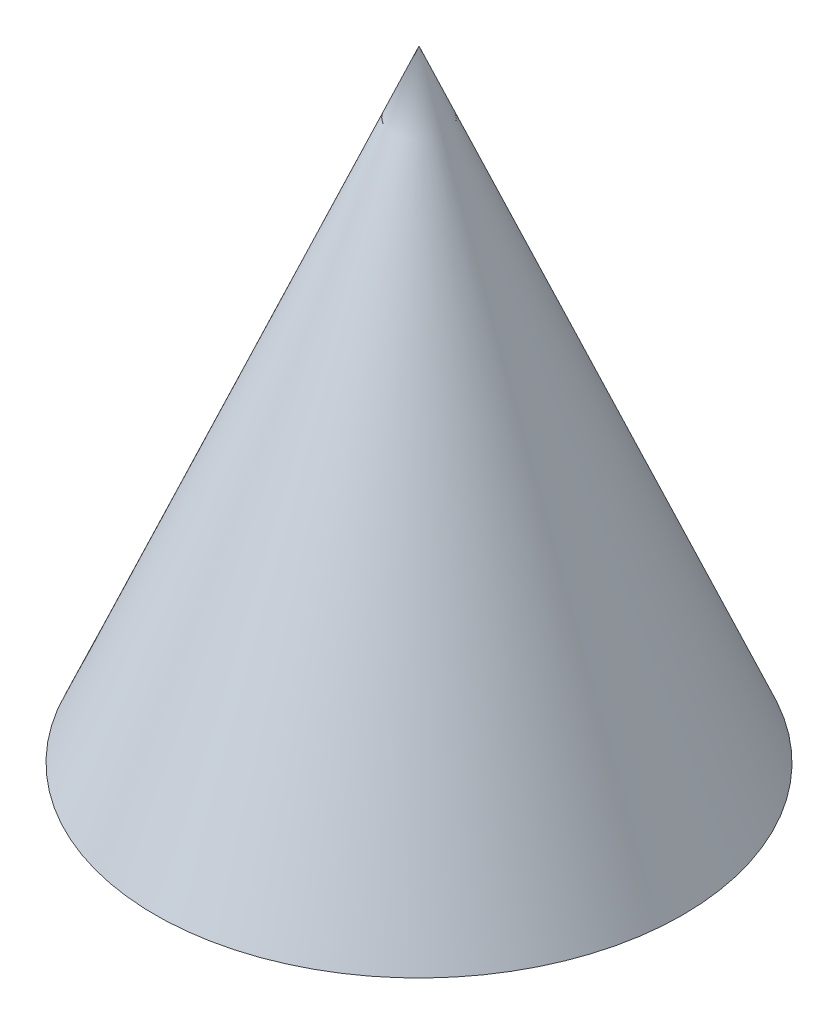
SolidWorks part; units mm, degrees
ref_plane "Front Plane" through (0, 0, 0) normal (0, 0, 1) x (1, 0, 0)
ref_plane "Top Plane" through (0, 0, 0) normal (0, 1, 0) x (1, 0, 0)
ref_plane "Right Plane" through (0, 0, 0) normal (1, 0, 0) x (0, 0, -1)
sketch "Sketch1" plane through (0, 0, 0) normal (0, 0, 1) x (1, 0, 0)
  line L0 (0, 0) -> (1700, 0)
  line L7 (1700, 0) -> (0, 4000)
  line L8 (0, 4000) -> (0, 0)
  dimension "D1" = 1700
  dimension "D2" = 4000
revolve "Revolve1" add sketch "Sketch1" angle 360 about L8
